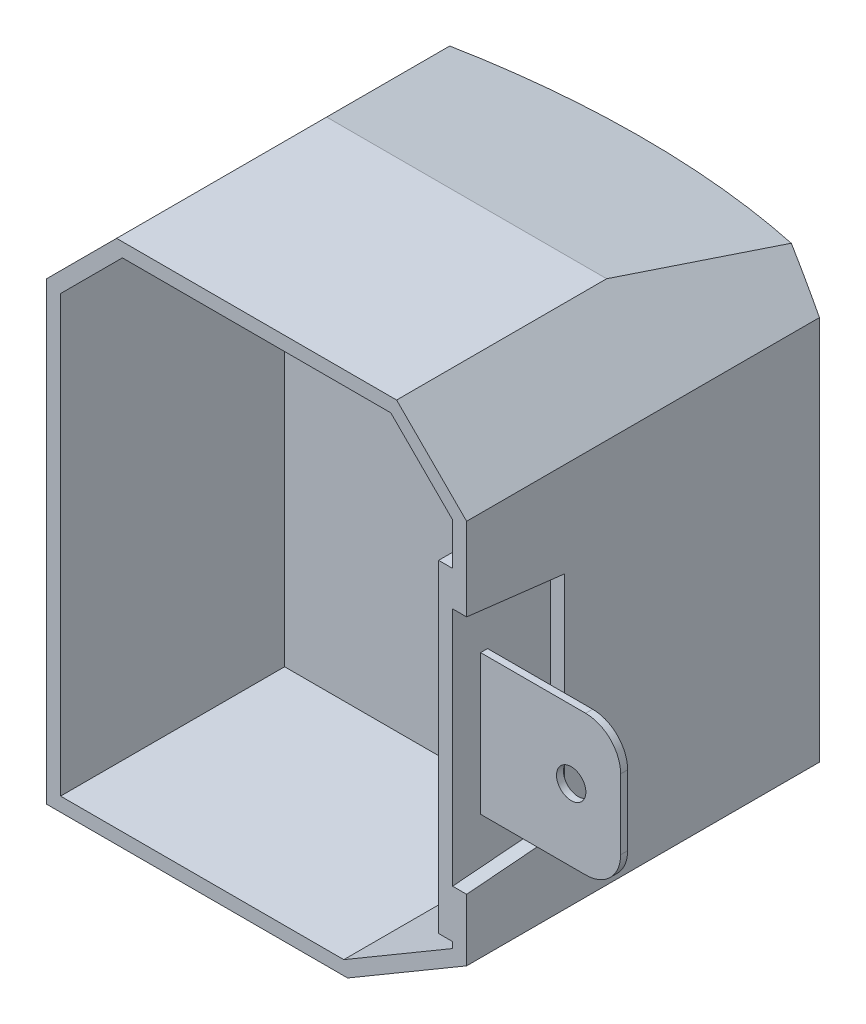
SolidWorks part; units mm, degrees
ref_plane "Спереди" through (0, 0, 0) normal (0, 0, 1) x (1, 0, 0)
ref_plane "Сверху" through (0, 0, 0) normal (0, 1, 0) x (1, 0, 0)
ref_plane "Справа" through (0, 0, 0) normal (1, 0, 0) x (0, 0, -1)
sketch "Эскиз1" plane through (0, 0, 0) normal (0, 0, 1) x (1, 0, 0)
  line L0 (0, 0) -> (60, 0)
  line L1 (60, 0) -> (60, 75)
  line L2 (60, 75) -> (0, 75)
  line L3 (0, 75) -> (0, 0)
extrude "Бобышка-Вытянуть1" add sketch "Эскиз1" along normal blind 55
sketch "Эскиз3" plane through (60, 0, 0) normal (1, 0, 0) x (0, 0, -1)
  line L0 (0, 0) -> (0, 10)
  line L1 (0, 0) -> (0, 75) construction
  line L2 (0, 75) -> (0, 70)
  line L3 (-20, 0) -> (0, 10)
  line L4 (-55, 0) -> (0, 0) construction
  line L5 (-20, 0) -> (0, 0)
  line L6 (0, 75) -> (-25, 75)
  line L7 (-55, 75) -> (0, 75) construction
  line L8 (-25, 75) -> (0, 70)
extrude "Вырез-Вытянуть2" cut sketch "Эскиз3" against normal blind 63
sketch "Эскиз4" plane through (0, 0, 0) normal (0, 0, -1) x (-1, 0, 0)
  line L0 (-60, 0) -> (-60, 10)
  line L1 (-60, 0) -> (-43, 0)
  line L2 (0, 0) -> (-60, 0) construction
  line L3 (-43, 0) -> (-60, 10)
extrude "Вырез-Вытянуть3" cut sketch "Эскиз4" against normal blind 63
sketch "Эскиз5" plane through (0, 0, 0) normal (0, 0, -1) x (-1, 0, 0)
  line L0 (-60, 75) -> (-60, 65)
  line L2 (-60, 10) -> (-60, 70) construction
  line L3 (-60, 75) -> (-50, 75)
  line L4 (0, 75) -> (-60, 75) construction
  line L5 (-50, 75) -> (-60, 65)
  line L7 (-30, 75) -> (-30, 86.231) construction
  line L8 (-10, 75) -> (0, 65)
  line L9 (0, 75) -> (-10, 75)
  line L10 (0, 75) -> (0, 65)
extrude "Вырез-Вытянуть4" cut sketch "Эскиз5" against normal blind 63
sketch "Эскиз6" plane through (0, 75, 0) normal (0, 1, 0) x (1, 0, 0)
  line L2 (0, 0) -> (60, 0)
  line L3 (0, 0) -> (0, -4.6061)
  line L5 (60, 0) -> (60, -4.6061)
  arc A0 (60, -4.6061) -> (0, -4.6061) centre (30, -100) ccw
extrude "Вырез-Вытянуть5" cut sketch "Эскиз6" against normal blind 73 contours A0 L2 L3 | A0 L5 L2
sketch "Эскиз7" plane through (0, 0, 55) normal (0, 0, 1) x (1, 0, 0)
  line L28 (58, 64.1716) -> (49.1716, 73)
  line L29 (49.1716, 73) -> (10.8284, 73)
  line L30 (10.8284, 73) -> (2, 64.1716)
  line L31 (2, 64.1716) -> (2, 2)
  line L32 (2, 2) -> (42.4554, 2)
  line L33 (42.4554, 2) -> (58, 11.1439)
  line L34 (58, 11.1439) -> (58, 64.1716)
  line L35 (58, 64.1716) -> (49.1716, 73)
  line L36 (49.1716, 73) -> (10.8284, 73)
  line L37 (10.8284, 73) -> (2, 64.1716)
  line L38 (2, 64.1716) -> (2, 2)
  line L39 (2, 2) -> (42.4554, 2)
  line L40 (42.4554, 2) -> (58, 11.1439)
  line L41 (58, 11.1439) -> (58, 64.1716)
  dimension "D2" = 2
extrude "Вырез-Вытянуть6" cut sketch "Эскиз7" against normal blind 32
sketch "Эскиз8" plane through (60, 0, 0) normal (1, 0, 0) x (0, 0, -1)
  line L0 (-55, 18.8548) -> (-55, 53.1661)
  line L1 (-55, 10) -> (-55, 65) construction
  line L2 (-41, 51.5) -> (-41, 20)
  line L3 (-41, 51.5) -> (-55, 53.1661)
  line L4 (-41, 20) -> (-55, 18.8548)
extrude "Вырез-Вытянуть7" cut sketch "Эскиз8" against normal blind 32
sketch "Эскиз9" plane through (58, 0, 0) normal (-1, 0, 0) x (0, 0, 1)
  line L0 (55, 53.1661) -> (55, 18.8548)
  line L2 (55, 53.1661) -> (55, 58.1661)
  line L3 (55, 65) -> (55, 0) construction
  line L4 (55, 58.1661) -> (30, 58.1661)
  line L5 (30, 58.1661) -> (30, 12.0041)
  line L6 (30, 12.0041) -> (55, 12.0041)
  line L7 (55, 12.0041) -> (55, 18.8548)
extrude "Бобышка-Вытянуть2" add sketch "Эскиз9" along normal blind 2
sketch "Эскиз10" plane through (58, 0, 0) normal (1, 0, 0) x (0, 0, -1)
  line L0 (-51, 45.75) -> (-51, 25.75)
  line L1 (-51, 25.75) -> (-50, 25.75)
  line L2 (-50, 25.75) -> (-50, 45.75)
  line L3 (-50, 45.75) -> (-51, 45.75)
  line L4 (-55, 18.8548) -> (-55, 53.1661) construction
  dimension "D1" = 20
  dimension "D2" = 1
  dimension "D3" = 4
  dimension "D4" = 5.75
extrude "Бобышка-Вытянуть3" add sketch "Эскиз10" along normal blind 20
fillet "Скругление1" radius 5 2 edges at (78, 25.75, 50.5) (78, 45.75, 50.5)
hole_wizard "Отверстие обработанное метчиком M51" positions "Эскиз11" profile "Эскиз12" tap size "M5" standard "ISO"
sketch "Эскиз11" plane through (0, 0, 50) normal (0, 0, -1) x (-1, 0, 0)
  point P0 (-70.9361, 36.0123)
sketch "Эскиз12" plane through (70.9361, 36.0123, 50) normal (1, 0, 0) x (0, 1, 0)
  line L0 (0, 0) -> (0, 39.7618)
  line L1 (0, 39.7618) -> (2.1, 38.5)
  line L2 (2.1, 38.5) -> (2.1, 0)
  line L5 (2.1, 0) -> (0, 0)
  line L10 (0, 39.7618) -> (-2.1, 38.5) construction
  line L11 (0, -6.35) -> (0, 107.95) construction
  dimension "Диаметр сверла" = 4.2
  dimension "Глубина сверла" = 38.5
  dimension "Угол заточки сверла" = 118
cosmetic thread "Отверстие резьбы1" parameters "D1"=1, "D2"=5
